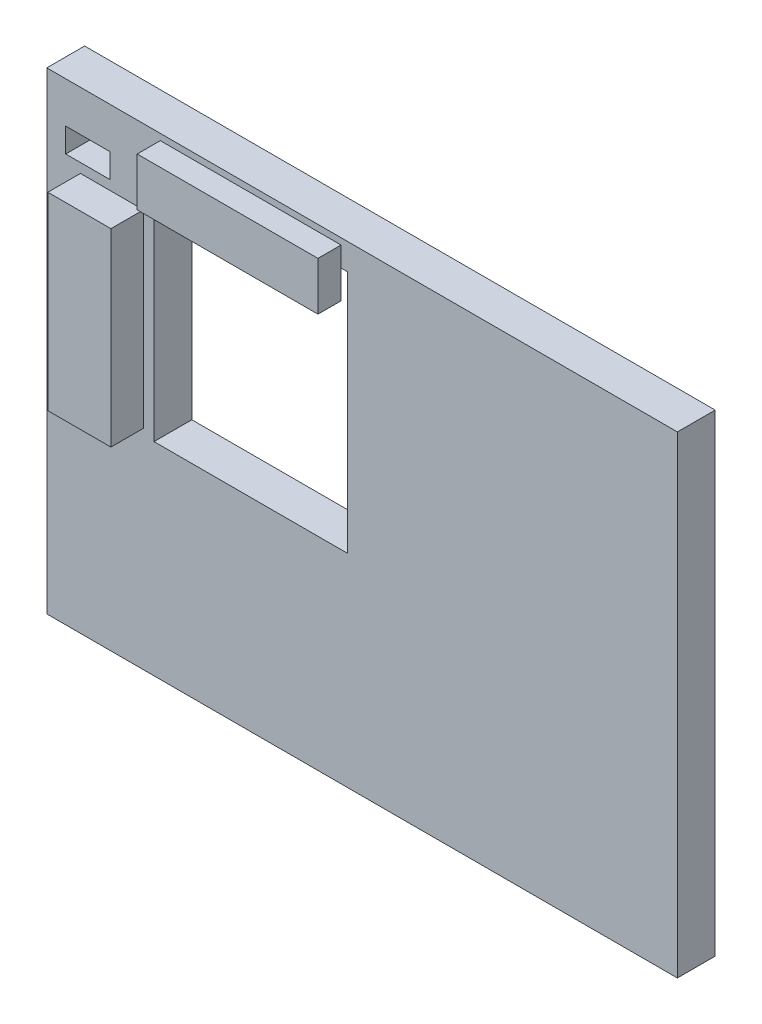
SolidWorks part; units mm, degrees
ref_plane "Front Plane" through (0, 0, 0) normal (0, 0, 1) x (1, 0, 0)
ref_plane "Top Plane" through (0, 0, 0) normal (0, 1, 0) x (1, 0, 0)
ref_plane "Right Plane" through (0, 0, 0) normal (1, 0, 0) x (0, 0, -1)
sketch "Sketch1" plane through (0, 0, 0) normal (0, 0, 1) x (1, 0, 0)
  line L1 (-1433.2932, 774.7195) -> (1566.7068, 774.7195)
  line L2 (-1433.2932, 774.7195) -> (-1433.2932, -1475.2805)
  line L3 (-1433.2932, -1475.2805) -> (1566.7068, -1475.2805)
  line L4 (1566.7068, 774.7195) -> (1566.7068, -1475.2805)
  line L5 (-1343.2932, 579.7195) -> (-1133.2932, 579.7195)
  line L6 (-1343.2932, 579.7195) -> (-1343.2932, 464.7195)
  line L7 (-1343.2932, 464.7195) -> (-1133.2932, 464.7195)
  line L8 (-1133.2932, 579.7195) -> (-1133.2932, 464.7195)
  line L9 (-923.2932, 649.7195) -> (-3.2932, 649.7195)
  line L10 (-923.2932, 649.7195) -> (-923.2932, -510.2805)
  line L11 (-923.2932, -510.2805) -> (-3.2932, -510.2805)
  line L12 (-3.2932, 649.7195) -> (-3.2932, -510.2805)
  dimension "D1" = 3000
  dimension "D2" = 2250
  dimension "D3" = 210
  dimension "D4" = 115
  dimension "D7" = 1160
  dimension "D8" = 920
  dimension "D9" = 125
  dimension "D10" = 195
  dimension "D11" = 90
  dimension "D12" = 210
extrude "Boss-Extrude1" add sketch "Sketch1" along normal blind 180
sketch "Sketch2" plane through (0, 0, 180) normal (0, 0, 1) x (1, 0, 0)
  line L1 (-1273.2932, 419.7195) -> (-973.2932, 419.7195)
  line L2 (-1273.2932, 419.7195) -> (-1273.2932, -480.2805)
  line L3 (-1273.2932, -480.2805) -> (-973.2932, -480.2805)
  line L4 (-973.2932, 419.7195) -> (-973.2932, -480.2805)
extrude "Boss-Extrude2" add sketch "Sketch2" along normal blind 155
sketch "Sketch3" plane through (0, 0, 180) normal (0, 0, 1) x (1, 0, 0)
  line L0 (-923.2932, 649.7195) -> (-923.2932, -510.2805) construction
  line L1 (-893.2932, 744.7195) -> (-33.2932, 744.7195)
  line L2 (-893.2932, 744.7195) -> (-893.2932, 514.7195)
  line L3 (-893.2932, 514.7195) -> (-33.2932, 514.7195)
  line L4 (-33.2932, 744.7195) -> (-33.2932, 514.7195)
  line L6 (1566.7068, 774.7195) -> (-1433.2932, 774.7195) construction
  dimension "D1" = 860
  dimension "D2" = 30
  dimension "D3" = 30
  dimension "D4" = 230
extrude "Boss-Extrude3" add sketch "Sketch3" along normal blind 110
